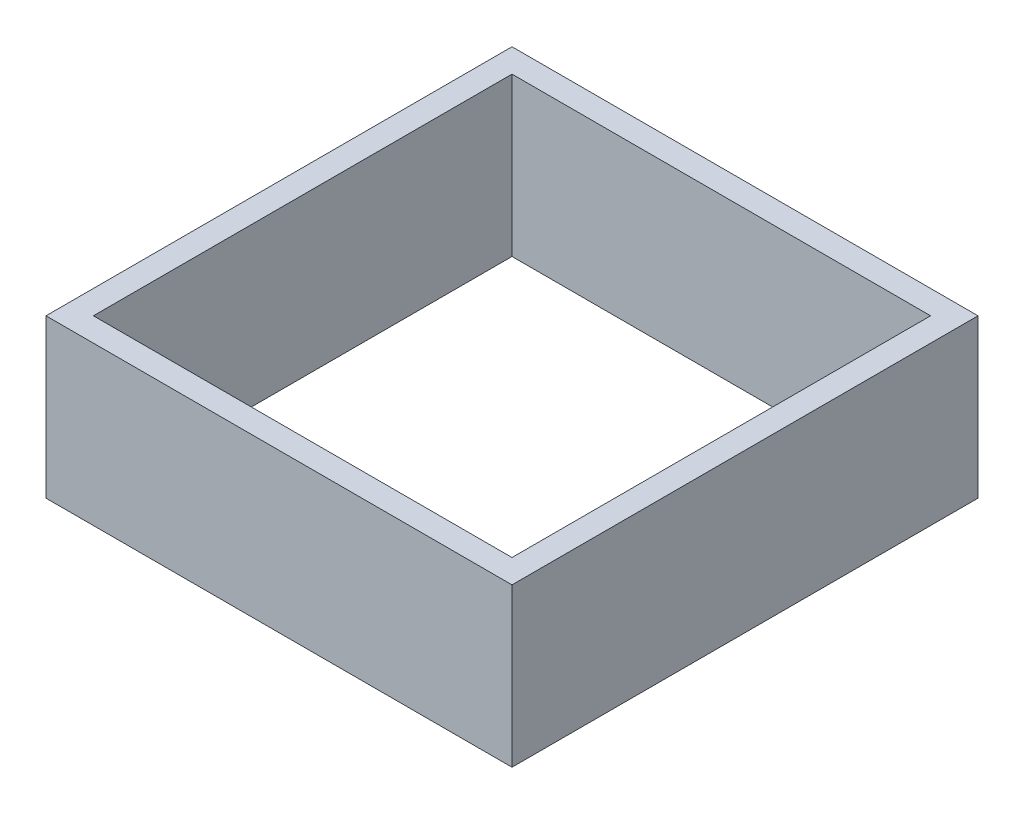
SolidWorks part; units mm, degrees
ref_plane "Front Plane" through (0, 0, 0) normal (0, 0, 1) x (1, 0, 0)
ref_plane "Top Plane" through (0, 0, 0) normal (0, 1, 0) x (1, 0, 0)
ref_plane "Right Plane" through (0, 0, 0) normal (1, 0, 0) x (0, 0, -1)
sketch "Sketch1" plane through (0, 0, 0) normal (0, 1, 0) x (1, 0, 0)
  line L1 (-29.5, -29.5) -> (29.5, -29.5)
  line L2 (-29.5, -29.5) -> (-29.5, 29.5)
  line L3 (-29.5, 29.5) -> (29.5, 29.5)
  line L4 (29.5, -29.5) -> (29.5, 29.5)
  line L5 (-29.5, -29.5) -> (29.5, 29.5) construction
  line L6 (-29.5, 29.5) -> (29.5, -29.5) construction
  line L7 (-26.5, -26.5) -> (26.5, -26.5)
  line L8 (-26.5, -26.5) -> (-26.5, 26.5)
  line L9 (-26.5, 26.5) -> (26.5, 26.5)
  line L10 (26.5, -26.5) -> (26.5, 26.5)
  line L11 (-26.5, -26.5) -> (26.5, 26.5) construction
  line L12 (-26.5, 26.5) -> (26.5, -26.5) construction
  point P0 (0, 0)
  point P6 (0, 0)
  dimension "D1" = 3
  dimension "D2" = 3
  dimension "D3" = 53
  dimension "D4" = 53
extrude "Boss-Extrude1" add sketch "Sketch1" along normal blind 20
